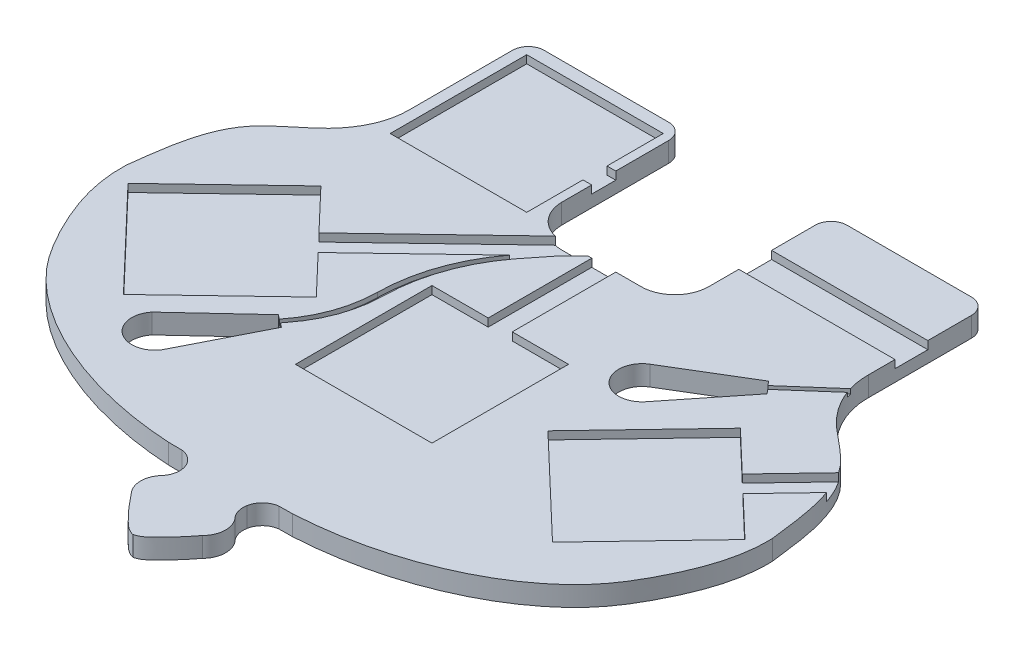
SolidWorks part; units mm, degrees
ref_plane "Front Plane" through (0, 0, 0) normal (0, 0, 1) x (1, 0, 0)
ref_plane "Top Plane" through (0, 0, 0) normal (0, 1, 0) x (1, 0, 0)
ref_plane "Right Plane" through (0, 0, 0) normal (1, 0, 0) x (0, 0, -1)
sketch "Sketch1" plane through (0, 0, 0) normal (0, 1, 0) x (1, 0, 0)
  line L32 (52.5446, 96) -> (92.3846, 96)
  line L41 (97.4646, 90.92) -> (97.4646, 57.9429)
  line L42 (0.5354, 90.92) -> (0.5354, 56.6931)
  line L43 (11.54, 46) -> (36.46, 46)
  line L44 (47.4646, 90.92) -> (47.4646, 56.6931)
  line L45 (-49.4646, 90.92) -> (-49.4646, 57.9429)
  line L46 (-4.5446, 96) -> (-44.3846, 96)
  arc A20 (39.5037, -72.7849) -> (34.256, -77.7131) centre (40.2477, -78.8351) ccw
  arc A21 (34.256, -77.7131) -> (35.4316, -82.7123) centre (40.5006, -78.8825) ccw
  arc A22 (35.4316, -82.7123) -> (35.4316, -93.1427) centre (30.2163, -87.9275) cw
  arc A23 (47.4646, 90.92) -> (52.5446, 96) centre (52.5446, 90.92) cw
  arc A24 (92.3846, 96) -> (97.4646, 90.92) centre (92.3846, 90.92) cw
  arc A26 (36.46, 46) -> (47.4646, 56.6931) centre (36.6158, 56.8489) ccw
  arc A27 (11.54, 46) -> (0.5354, 56.6931) centre (11.3842, 56.8489) cw
  arc A28 (-44.3846, 96) -> (-49.4646, 90.92) centre (-44.3846, 90.92) ccw
  arc A29 (0.5354, 90.92) -> (-4.5446, 96) centre (-4.5446, 90.92) ccw
  arc A30 (12.5684, -82.7123) -> (12.5684, -93.1427) centre (17.7837, -87.9275) ccw
  arc A31 (13.744, -77.7131) -> (12.5684, -82.7123) centre (7.4994, -78.8825) cw
  arc A32 (8.4963, -72.7849) -> (13.744, -77.7131) centre (7.7523, -78.8351) cw
  spline S0 degree 3 poles (127.446, -2.7574) (127.823, -13.0979) (122.8805, -26.6657) (112.7753, -43.7052) (101.2163, -54.3469) (78.6436, -67.2734) (58.3173, -71.9175) (43.8553, -72.7417) knots 0 0 0 0 0.251848 0.354065 0.492006 0.637696 1 1 1 1
  spline S1 degree 3 poles (-79.446, -2.7574) (-78.2174, 6.7729) (-76.5279, 26.9375) (-55.1988, 39.1209) (-49.373, 51.4164) (-49.4646, 57.9429) knots 0 0 0 0 0.454201 0.725734 1 1 1 1
  spline S2 degree 1 poles (43.8553, -72.7417) (39.5037, -72.7849) knots 0 0 1 1
  spline S3 degree 3 poles (35.4316, -93.1427) (33.3162, -95.9519) (29.837, -99.8342) (25.8351, -103.5985) (24, -104.0157) knots 0 0 0 0 0.654699 1 1 1 1
  spline S4 degree 3 poles (127.446, -2.7574) (126.2174, 6.7729) (124.5279, 26.9375) (103.1988, 39.1209) (97.373, 51.4164) (97.4646, 57.9429) knots 0 0 0 0 0.454201 0.725734 1 1 1 1
  spline S5 degree 3 poles (12.5684, -93.1427) (14.6838, -95.9519) (18.163, -99.8342) (22.1649, -103.5985) (24, -104.0157) knots 0 0 0 0 0.654699 1 1 1 1
  spline S6 degree 1 poles (4.1447, -72.7417) (8.4963, -72.7849) knots 0 0 1 1
  spline S7 degree 3 poles (-79.446, -2.7574) (-79.823, -13.0979) (-74.8805, -26.6657) (-64.7753, -43.7052) (-53.2163, -54.3469) (-30.6436, -67.2734) (-10.3173, -71.9175) (4.1447, -72.7417) knots 0 0 0 0 0.251848 0.354065 0.492006 0.637696 1 1 1 1
extrude "Boss-Extrude1" add sketch "Sketch1" along normal blind 6.35
sketch "Sketch2" plane through (0, 6.35, 0) normal (0, 1, 0) x (1, 0, 0)
  line L0 (-4.5446, 96) -> (-44.3846, 96) construction
  line L1 (-45.9646, 92) -> (-2.2646, 92)
  line L2 (-45.9646, 92) -> (-45.9646, 48.3)
  line L3 (-45.9646, 48.3) -> (-2.2646, 48.3)
  line L4 (-2.2646, 92) -> (-2.2646, 48.3)
  line L5 (-49.4646, 90.92) -> (-49.4646, 57.9429) construction
  line L11 (2.8496, 12.856) -> (46.5496, 12.856)
  line L12 (2.8496, 12.856) -> (2.8496, -30.844)
  line L13 (46.5496, 12.856) -> (46.5496, -30.844)
  line L14 (2.8496, -30.844) -> (46.5496, -30.844)
  line L19 (91.756, 22.664) -> (61.6874, -8.87)
  line L24 (61.6874, -8.87) -> (93.2878, -39.0019)
  line L25 (93.2878, -39.0019) -> (123.3564, -7.468)
  line L26 (123.3564, -7.468) -> (91.756, 22.664)
  line L32 (-44.0433, -39.0019) -> (-74.112, -7.468)
  line L33 (-12.443, -8.87) -> (-44.0433, -39.0019)
  line L34 (-42.5116, 22.664) -> (-12.443, -8.87)
  line L35 (-74.112, -7.468) -> (-42.5116, 22.664)
  dimension "D1" = 43.7
  dimension "D2" = 43.7
  dimension "D3" = 4
  dimension "D4" = 3.5
  dimension "D5" = 15.1378
  dimension "D6" = 5.334
  dimension "D7" = 4.0896
  dimension "D8" = 43.7
sketch "Sketch4" plane through (0, 6.35, 0) normal (0, 1, 0) x (1, 0, 0)
  line L3 (-2.2646, 74) -> (0.5354, 74)
  line L5 (0.5354, 56.6931) -> (0.5354, 90.92) construction
  line L6 (-2.2646, 66.3) -> (0.5354, 66.3)
  line L7 (-2.2646, 74) -> (-2.2646, 66.3)
  line L8 (0.5354, 74) -> (0.5354, 66.3)
  line L27 (20.85, 12.472) -> (28.55, 12.472)
  line L29 (20.85, 46) -> (28.55, 46)
  line L30 (28.55, 12.472) -> (28.55, 46)
  line L31 (36.46, 46) -> (11.54, 46) construction
  line L32 (20.85, 12.472) -> (20.85, 46)
  point P21 (25.035, 48.595)
  dimension "D1" = 33.528
extrude "Cut-Extrude1" cut sketch "Sketch2" against normal blind 2.54
sketch "Sketch5" plane through (0, 6.35, 0) normal (0, 1, 0) x (1, 0, 0)
  line L2 (104.7699, 10.2549) -> (122.2266, 28.5623)
  line L6 (123.3564, -7.468) -> (91.756, 22.664) construction
  line L8 (110.3425, 4.9411) -> (128.1471, 23.6133)
  line L9 (123.3564, -7.468) -> (91.756, 22.664) construction
  line L19 (-12.443, -8.87) -> (-42.5116, 22.664) construction
  line L21 (11.5225, 48.7863) -> (-29.8255, 9.3597)
  line L22 (-29.8255, 9.3597) -> (-24.5118, 3.787)
  line L23 (16.8362, 43.2137) -> (-24.5118, 3.787)
  line L24 (16.8362, 43.2137) -> (19.7583, 46)
  line L25 (36.46, 46) -> (11.54, 46) construction
  line L26 (19.7583, 46) -> (11.5225, 48.7863)
  line L35 (104.7699, 10.2549) -> (110.3425, 4.9411)
  line L36 (122.2266, 28.5623) -> (128.1471, 23.6133)
  point P11 (107.5562, 7.598)
  dimension "D1" = 3.85
  dimension "D2" = 3.85
extrude "Cut-Extrude3" cut sketch "Sketch5" against normal blind 2.54
extrude "Cut-Extrude4" cut sketch "Sketch4" against normal blind 2.54
sketch "Sketch6" plane through (0, 6.35, 0) normal (0, 1, 0) x (1, 0, 0)
  line L0 (86.5063, 36.4588) -> (69.3057, 14.8628)
  line L5 (83.2076, 40.2164) -> (59.5657, 25.9577)
  line L11 (-10.8902, -21.8945) -> (-9.655, -22.8254)
  line L18 (-9.655, -22.8254) -> (-22.6405, -48.3563)
  line L19 (83.2076, 40.2164) -> (86.5063, 36.4588)
  line L23 (-13.6482, -19.8163) -> (-34.6108, -39.3361)
  line L25 (-12.4758, -20.6998) -> (-13.6482, -19.8163)
  line L35 (-12.4758, -20.6998) -> (-10.8902, -21.8945)
  arc A7 (59.5657, 25.9577) -> (69.3057, 14.8628) centre (63.4391, 19.5354) ccw
  arc A14 (-34.6108, -39.3361) -> (-22.6405, -48.3563) centre (-28.8033, -44.0819) ccw
  dimension "D1" = 5.08
  dimension "D2" = 15.24
extrude "Cut-Extrude6" cut sketch "Sketch6" against normal through all
sketch "Sketch8" plane through (0, 6.35, 0) normal (0, 1, 0) x (1, 0, 0)
  line L5 (-24.5118, 3.787) -> (19.7583, 46) construction
  line L6 (-13.6482, -19.8163) -> (-9.655, -22.8254) construction
  line L7 (-11.0526, -21.7722) -> (-10.2983, -20.773)
  line L8 (8.7859, 33.5779) -> (15.2128, 41.6657)
  line L10 (-12.2511, -20.8691) -> (-11.0526, -21.7722)
  line L12 (6.8354, 33.6776) -> (15.2128, 41.6657)
  line L13 (84.3622, 38.9012) -> (101.4701, 53.9198)
  line L14 (83.2076, 40.2164) -> (86.5063, 36.4588) construction
  line L15 (85.3518, 37.774) -> (102.6199, 52.9332)
  line L16 (84.3622, 38.9012) -> (85.3518, 37.774)
  line L17 (101.4701, 53.9198) -> (102.6199, 52.9332)
  arc A0 (-12.2511, -20.8691) -> (-4.0016, 2.2011) centre (-41.5357, 2.6127) ccw
  arc A1 (-10.2983, -20.773) -> (-2.0511, 2.1015) centre (-39.5826, 2.7091) ccw
  arc A2 (-4.0016, 2.2011) -> (6.8354, 33.6776) centre (48.8113, 1.622) cw
  arc A3 (-2.0511, 2.1015) -> (8.7859, 33.5779) centre (50.7618, 1.5224) cw
  point P4 (84.857, 38.3376)
  point P11 (-11.6516, -21.3208)
  dimension "D1" = 0.75
  dimension "D2" = 0.75
  dimension "D3" = 0
  dimension "D4" = 0.75
extrude "Cut-Extrude7" cut sketch "Sketch8" against normal blind 1.5 contours A1 A3 L8 L12 A2 A0 L10 L7 | L15 L17 L13 L16
sketch "Sketch9" plane through (0, 6.35, 0) normal (0, 1, 0) x (1, 0, 0)
  line L0 (47.4646, 90.92) -> (47.4646, 56.6931) construction
  line L1 (47.4646, 76.95) -> (97.4646, 76.95)
  line L2 (47.4646, 76.95) -> (47.4646, 66.45)
  line L3 (47.4646, 66.45) -> (97.4646, 66.45)
  line L4 (97.4646, 76.95) -> (97.4646, 66.45)
  line L5 (97.4646, 57.9429) -> (97.4646, 90.92) construction
  line L6 (92.3846, 96) -> (52.5446, 96) construction
  dimension "D1" = 10.5
  dimension "D2" = 19.05
extrude "Cut-Extrude8" cut sketch "Sketch9" against normal blind 2.54
